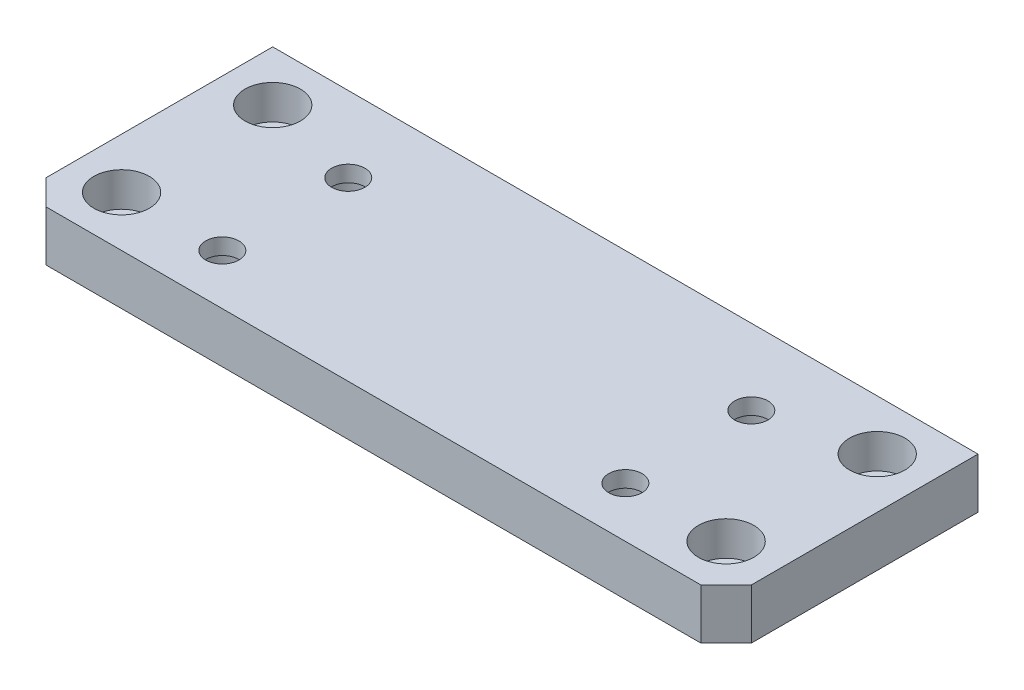
SolidWorks part; units mm, degrees
material "1060 Alloy"
ref_plane "Front Plane" through (0, 0, 0) normal (0, 0, 1) x (1, 0, 0)
ref_plane "Top Plane" through (0, 0, 0) normal (0, 1, 0) x (1, 0, 0)
ref_plane "Right Plane" through (0, 0, 0) normal (1, 0, 0) x (0, 0, -1)
sketch "Sketch1" plane through (0, 0, 0) normal (0, 1, 0) x (1, 0, 0)
  line L1 (70, -25) -> (-70, -25)
  line L2 (70, -25) -> (70, 25)
  line L3 (70, 25) -> (-70, 25)
  line L4 (-70, -25) -> (-70, 25)
  line L5 (70, -25) -> (-70, 25) construction
  line L6 (70, 25) -> (-70, -25) construction
  point P0 (0, 0)
  dimension "D1" = 50
  dimension "D2" = 140
extrude "Boss-Extrude1" add sketch "Sketch1" along normal blind 10
hole_wizard "CBORE for M6 Hexagon socket head cap screws1" positions "Sketch2" profile "Sketch4" counterbore size "M6" standard "GB" end condition through all
sketch "Sketch2" plane through (0, 10, 0) normal (0, 1, 0) x (1, 0, 0)
  line L0 (0, -5.5) -> (0, 5.5) construction
  line L1 (-5.5, 0) -> (5.5, 0) construction
  point P0 (-60, 15)
  point P7 (60, 15)
  point P10 (60, -15)
  point P11 (-60, -15)
  dimension "D1" = 120
  dimension "D2" = 30
sketch "Sketch4" plane through (-60, 10, -15) normal (1, 0, 0) x (0, 0, 1)
  line L0 (0, 0) -> (0, 10)
  line L1 (0, 10) -> (3.3, 10)
  line L3 (3.3, 10) -> (3.3, 6.8)
  line L4 (3.3, 6.8) -> (5.5, 6.8)
  line L5 (5.5, 6.8) -> (5.5, 0)
  line L7 (5.5, 0) -> (0, 0)
  line L11 (0, -6.35) -> (0, 107.95) construction
  dimension "Thru Hole Dia." = 6.6
  dimension "Thru Hole Depth" = 10
  dimension "C'Bore Dia." = 11
  dimension "C'Bore Depth" = 6.8
hole_wizard "CBORE for M6 Hexagon socket head cap screws2" positions "Sketch5" profile "Sketch6" counterbore size "M6" standard "GB" end condition through all
sketch "Sketch5" plane through (0, 0, 0) normal (0, -1, 0) x (-1, 0, 0)
  line L0 (0, 5.5) -> (0, -5.5) construction
  line L1 (-70, 25) -> (70, 25) construction
  line L2 (70, -25) -> (-70, -25) construction
  point P0 (-40, 10)
  point P4 (-40, -15)
  point P9 (40, -15)
  point P10 (40, 10)
  dimension "D1" = 15
  dimension "D2" = 10
  dimension "D3" = 80
sketch "Sketch6" plane through (40, 0, -10) normal (1, 0, 0) x (0, 0, -1)
  line L0 (0, 0) -> (0, 10)
  line L1 (0, 10) -> (3.3, 10)
  line L3 (3.3, 10) -> (3.3, 6.8)
  line L4 (3.3, 6.8) -> (5.5, 6.8)
  line L5 (5.5, 6.8) -> (5.5, 0)
  line L7 (5.5, 0) -> (0, 0)
  line L11 (0, -6.35) -> (0, 107.95) construction
  dimension "Thru Hole Dia." = 6.6
  dimension "Thru Hole Depth" = 10
  dimension "C'Bore Dia." = 11
  dimension "C'Bore Depth" = 6.8
chamfer "Chamfer1" distance 5 angle 45 2 edges at (-70, 5, 25) (70, 5, 25)
